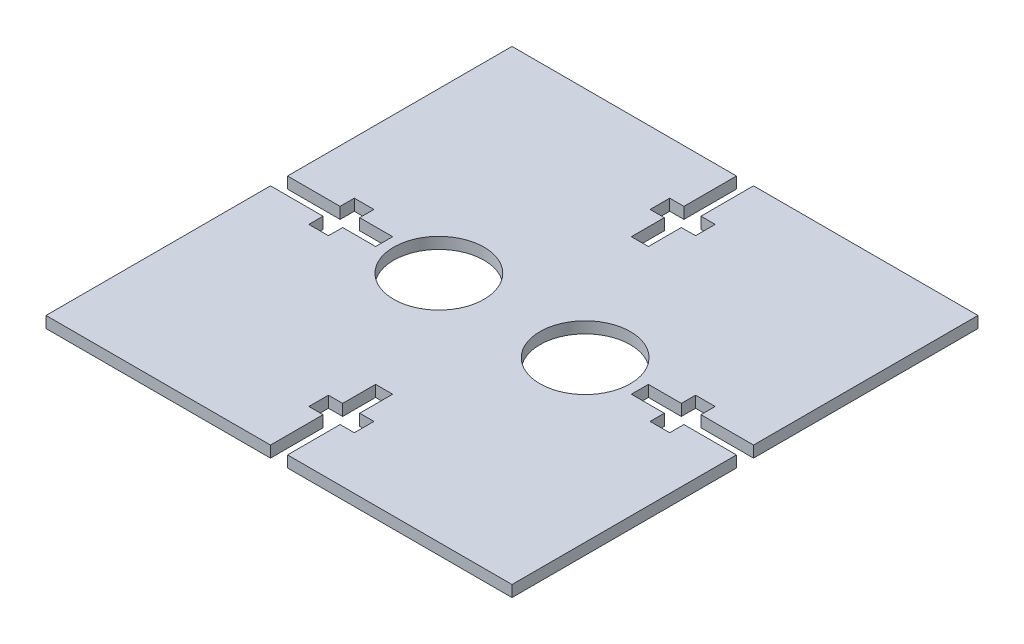
SolidWorks part; units mm, degrees
ref_plane "Front Plane" through (0, 0, 0) normal (0, 0, 1) x (1, 0, 0)
ref_plane "Top Plane" through (0, 0, 0) normal (0, 1, 0) x (1, 0, 0)
ref_plane "Right Plane" through (0, 0, 0) normal (1, 0, 0) x (0, 0, -1)
sketch "Sketch1" plane through (0, 0, 0) normal (0, 1, 0) x (1, 0, 0)
  line L1 (-41, -41) -> (41, -41)
  line L2 (-41, -41) -> (-41, 41)
  line L3 (-41, 41) -> (41, 41)
  line L4 (41, -41) -> (41, 41)
  line L5 (-41, -41) -> (41, 41) construction
  line L6 (-41, 41) -> (41, -41) construction
  point P0 (0, 0)
  dimension "D1" = 82
  dimension "D2" = 82
extrude "Boss-Extrude1" add sketch "Sketch1" along normal blind 2
sketch "Sketch2" plane through (0, 2, 0) normal (0, 1, 0) x (1, 0, 0)
  line L0 (-20.825, 0) -> (20.825, 0) construction
  line L1 (41, 41) -> (-41, 41) construction
  line L2 (41, -41) -> (41, 41) construction
  circle A0 centre (-12.87, 0) radius 7.955
  circle A1 centre (12.87, 0) radius 7.955
  point P8 (0, 0)
  dimension "D1" = 15.91
  dimension "D2" = 15.91
  dimension "D4" = 41
  dimension "D5" = 41
  dimension "D3" = 41.65
  dimension "D6" = 41
extrude "Cut-Extrude1" cut sketch "Sketch2" against normal blind 10 contours A1 | A0
sketch "Sketch6" plane through (0, 2, 0) normal (0, 1, 0) x (1, 0, 0)
  line L0 (0, 0) -> (0, 41) construction
  line L1 (41, 41) -> (-41, 41) construction
  line L3 (-1.5, 22.5) -> (1.5, 22.5)
  line L4 (-1.5, 22.5) -> (-1.5, 28.3)
  line L5 (-1.5, 41) -> (1.5, 41)
  line L6 (1.5, 22.5) -> (1.5, 28.3)
  line L7 (-1.5, 22.5) -> (1.5, 41) construction
  line L8 (-1.5, 41) -> (1.5, 22.5) construction
  line L9 (1.5, 31.75) -> (4, 31.75)
  line L10 (4, 31.75) -> (4, 28.3)
  line L11 (4, 28.3) -> (1.5, 28.3)
  line L13 (-1.5, 28.3) -> (-4, 28.3)
  line L14 (-4, 28.3) -> (-4, 31.75)
  line L15 (-4, 31.75) -> (-1.5, 31.75)
  line L16 (-1.5, 31.75) -> (-1.5, 41)
  line L17 (1.5, 31.75) -> (1.5, 41)
  line L90 (28.3, 1.5) -> (28.3, 4)
  line L91 (28.3, 4) -> (31.75, 4)
  line L92 (31.75, 4) -> (31.75, 1.5)
  line L93 (31.75, 1.5) -> (41, 1.5)
  line L94 (41, 1.5) -> (41, -1.5)
  line L95 (31.75, -1.5) -> (41, -1.5)
  line L96 (31.75, -1.5) -> (31.75, -4)
  line L97 (31.75, -4) -> (28.3, -4)
  line L98 (28.3, -4) -> (28.3, -1.5)
  line L99 (22.5, -1.5) -> (28.3, -1.5)
  line L100 (22.5, 1.5) -> (22.5, -1.5)
  line L101 (22.5, 1.5) -> (28.3, 1.5)
  line L102 (1.5, -28.3) -> (4, -28.3)
  line L103 (4, -28.3) -> (4, -31.75)
  line L104 (4, -31.75) -> (1.5, -31.75)
  line L105 (1.5, -31.75) -> (1.5, -41)
  line L106 (1.5, -41) -> (-1.5, -41)
  line L107 (-1.5, -31.75) -> (-1.5, -41)
  line L108 (-1.5, -31.75) -> (-4, -31.75)
  line L109 (-4, -31.75) -> (-4, -28.3)
  line L110 (-4, -28.3) -> (-1.5, -28.3)
  line L111 (-1.5, -22.5) -> (-1.5, -28.3)
  line L112 (1.5, -22.5) -> (-1.5, -22.5)
  line L113 (1.5, -22.5) -> (1.5, -28.3)
  line L114 (-28.3, -1.5) -> (-28.3, -4)
  line L115 (-28.3, -4) -> (-31.75, -4)
  line L116 (-31.75, -4) -> (-31.75, -1.5)
  line L117 (-31.75, -1.5) -> (-41, -1.5)
  line L118 (-41, -1.5) -> (-41, 1.5)
  line L119 (-31.75, 1.5) -> (-41, 1.5)
  line L120 (-31.75, 1.5) -> (-31.75, 4)
  line L121 (-31.75, 4) -> (-28.3, 4)
  line L122 (-28.3, 4) -> (-28.3, 1.5)
  line L123 (-22.5, 1.5) -> (-28.3, 1.5)
  line L124 (-22.5, -1.5) -> (-22.5, 1.5)
  line L125 (-22.5, -1.5) -> (-28.3, -1.5)
  point P5 (0, 31.75)
  point P57 (0, 0)
  dimension "D1" = 3
  dimension "D2" = 18.5
  dimension "D3" = 4
  dimension "D4" = 2.5
  dimension "D5" = 2.5
  dimension "D6" = 3.45
extrude "Cut-Extrude4" cut sketch "Sketch6" against normal blind 10
